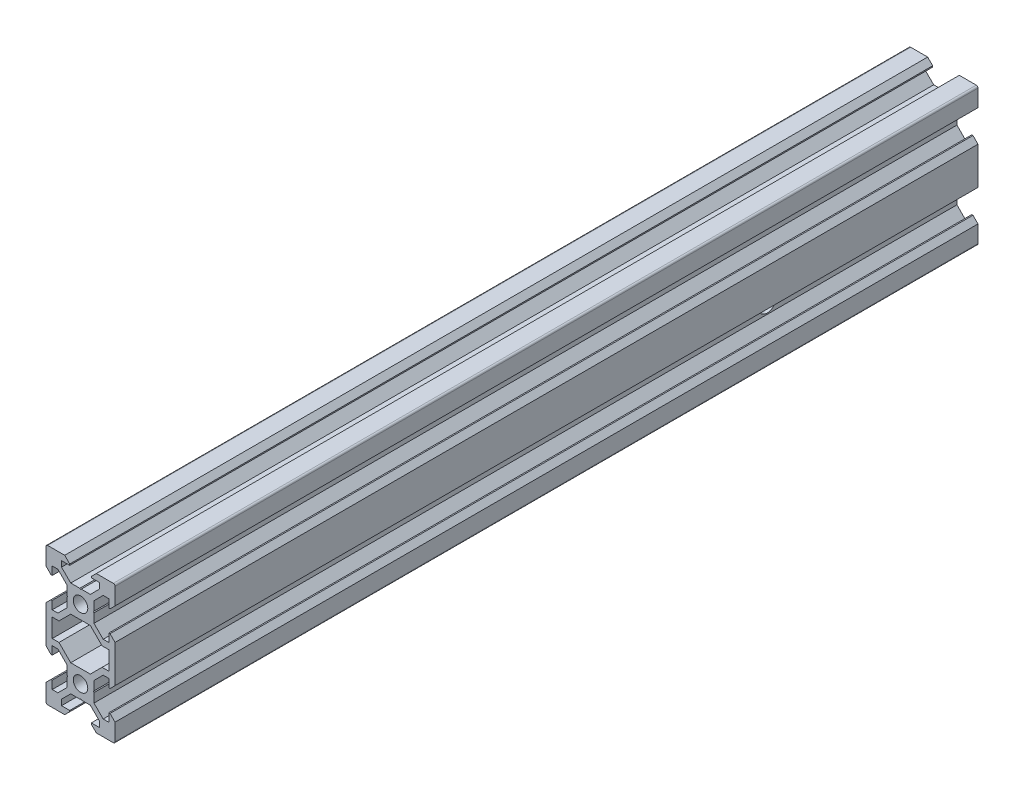
SolidWorks part; units mm, degrees
ref_plane "Plano frontal" through (0, 0, 0) normal (0, 0, 1) x (1, 0, 0)
ref_plane "Plano superior" through (0, 0, 0) normal (0, 1, 0) x (1, 0, 0)
ref_plane "Plano direito" through (0, 0, 0) normal (1, 0, 0) x (0, 0, -1)
sketch "Esboço1" plane through (0, 0, 0) normal (0, 0, 1) x (1, 0, 0)
  line L0 (8.2, -2.7) -> (8.2, 2.7)
  line L1 (8.2, 2.7) -> (6.2393, 2.7)
  line L2 (6.2393, 2.7) -> (2.8393, 6.1)
  line L3 (-2.8393, 6.1) -> (2.8393, 6.1)
  line L4 (-6.2393, 2.7) -> (-2.8393, 6.1)
  line L5 (-8.2, 2.7) -> (-6.2393, 2.7)
  line L6 (-8.2, -2.7) -> (-8.2, 2.7)
  line L7 (-8.2, -2.7) -> (-6.2393, -2.7)
  line L8 (-6.2393, -2.7) -> (-2.8393, -6.1)
  line L9 (-2.8393, -6.1) -> (2.8393, -6.1)
  line L10 (6.2393, -2.7) -> (2.8393, -6.1)
  line L11 (8.2, -2.7) -> (6.2393, -2.7)
  line L12 (3.9, 9.79) -> (3.69, 10)
  line L13 (3.69, 10) -> (3.9, 10.21)
  line L14 (3.9, 10.21) -> (3.9, 12.8393)
  line L15 (3.9, 12.8393) -> (6.5607, 15.5)
  line L16 (6.5607, 15.5) -> (8.2, 15.5)
  line L17 (8.2, 15.5) -> (8.2, 13.125)
  line L18 (8.2, 13.125) -> (8.545, 13.125)
  line L19 (8.545, 13.125) -> (10, 14.58)
  line L20 (10, 14.58) -> (10, 19.5)
  line L21 (9.5, 20) -> (4.58, 20)
  line L22 (4.58, 20) -> (3.125, 18.545)
  line L23 (3.125, 18.545) -> (3.125, 18.2)
  line L24 (3.125, 18.2) -> (5.5, 18.2)
  line L25 (5.5, 18.2) -> (5.5, 16.5607)
  line L26 (5.5, 16.5607) -> (2.8393, 13.9)
  line L27 (2.8393, 13.9) -> (0.21, 13.9)
  line L28 (0.21, 13.9) -> (0, 13.69)
  line L29 (0, 13.69) -> (-0.21, 13.9)
  line L30 (-0.21, 13.9) -> (-2.8393, 13.9)
  line L31 (-2.8393, 13.9) -> (-5.5, 16.5607)
  line L32 (-5.5, 16.5607) -> (-5.5, 18.2)
  line L33 (-5.5, 18.2) -> (-3.125, 18.2)
  line L34 (-3.125, 18.2) -> (-3.125, 18.545)
  line L35 (-3.125, 18.545) -> (-4.58, 20)
  line L36 (-4.58, 20) -> (-9.5, 20)
  line L37 (-10, 19.5) -> (-10, 14.58)
  line L38 (-10, 14.58) -> (-8.545, 13.125)
  line L39 (-8.545, 13.125) -> (-8.2, 13.125)
  line L40 (-8.2, 13.125) -> (-8.2, 15.5)
  line L41 (-8.2, 15.5) -> (-6.5607, 15.5)
  line L42 (-6.5607, 15.5) -> (-3.9, 12.8393)
  line L43 (-3.9, 12.8393) -> (-3.9, 10.21)
  line L44 (-3.9, 10.21) -> (-3.69, 10)
  line L45 (-3.69, 10) -> (-3.9, 9.79)
  line L46 (-3.9, 9.79) -> (-3.9, 7.1607)
  line L47 (-3.9, 7.1607) -> (-6.5607, 4.5)
  line L48 (-6.5607, 4.5) -> (-8.2, 4.5)
  line L49 (-8.2, 4.5) -> (-8.2, 6.875)
  line L50 (-8.2, 6.875) -> (-8.545, 6.875)
  line L51 (-8.545, 6.875) -> (-10, 5.42)
  line L52 (-10, 5.42) -> (-10, -5.42)
  line L53 (-10, -5.42) -> (-8.545, -6.875)
  line L54 (-8.545, -6.875) -> (-8.2, -6.875)
  line L55 (-8.2, -6.875) -> (-8.2, -4.5)
  line L56 (-8.2, -4.5) -> (-6.5607, -4.5)
  line L57 (-6.5607, -4.5) -> (-3.9, -7.1607)
  line L58 (-3.9, -7.1607) -> (-3.9, -9.79)
  line L59 (-3.9, -9.79) -> (-3.69, -10)
  line L60 (-3.69, -10) -> (-3.9, -10.21)
  line L61 (-3.9, -10.21) -> (-3.9, -12.8393)
  line L62 (-3.9, -12.8393) -> (-6.5607, -15.5)
  line L63 (-6.5607, -15.5) -> (-8.2, -15.5)
  line L64 (-8.2, -15.5) -> (-8.2, -13.125)
  line L65 (-8.2, -13.125) -> (-8.545, -13.125)
  line L66 (-8.545, -13.125) -> (-10, -14.58)
  line L67 (-10, -14.58) -> (-10, -19.5)
  line L68 (-9.5, -20) -> (-4.58, -20)
  line L69 (-4.58, -20) -> (-3.125, -18.545)
  line L70 (-3.125, -18.545) -> (-3.125, -18.2)
  line L71 (-3.125, -18.2) -> (-5.5, -18.2)
  line L72 (-5.5, -18.2) -> (-5.5, -16.5607)
  line L73 (-5.5, -16.5607) -> (-2.8393, -13.9)
  line L74 (-2.8393, -13.9) -> (-0.21, -13.9)
  line L75 (-0.21, -13.9) -> (0, -13.69)
  line L76 (0, -13.69) -> (0.21, -13.9)
  line L77 (0.21, -13.9) -> (2.8393, -13.9)
  line L78 (2.8393, -13.9) -> (5.5, -16.5607)
  line L79 (5.5, -16.5607) -> (5.5, -18.2)
  line L80 (5.5, -18.2) -> (3.125, -18.2)
  line L81 (3.125, -18.2) -> (3.125, -18.545)
  line L82 (3.125, -18.545) -> (4.58, -20)
  line L83 (4.58, -20) -> (9.5, -20)
  line L84 (10, -19.5) -> (10, -14.58)
  line L85 (10, -14.58) -> (8.545, -13.125)
  line L86 (8.545, -13.125) -> (8.2, -13.125)
  line L87 (8.2, -13.125) -> (8.2, -15.5)
  line L88 (8.2, -15.5) -> (6.5607, -15.5)
  line L89 (6.5607, -15.5) -> (3.9, -12.8393)
  line L90 (3.9, -12.8393) -> (3.9, -10.21)
  line L91 (3.9, -10.21) -> (3.69, -10)
  line L92 (3.69, -10) -> (3.9, -9.79)
  line L93 (3.9, -9.79) -> (3.9, -7.1607)
  line L94 (3.9, -7.1607) -> (6.5607, -4.5)
  line L95 (6.5607, -4.5) -> (8.2, -4.5)
  line L96 (8.2, -4.5) -> (8.2, -6.875)
  line L97 (8.2, -6.875) -> (8.545, -6.875)
  line L98 (8.545, -6.875) -> (10, -5.42)
  line L99 (10, -5.42) -> (10, 5.42)
  line L100 (10, 5.42) -> (8.545, 6.875)
  line L101 (8.545, 6.875) -> (8.2, 6.875)
  line L102 (8.2, 6.875) -> (8.2, 4.5)
  line L103 (8.2, 4.5) -> (6.5607, 4.5)
  line L104 (6.5607, 4.5) -> (3.9, 7.1607)
  line L105 (3.9, 7.1607) -> (3.9, 9.79)
  circle A0 centre (0, -10) radius 2.1
  circle A1 centre (0, 10) radius 2.1
  arc A2 (10, 19.5) -> (9.5, 20) centre (9.5, 19.5) ccw
  arc A3 (-9.5, 20) -> (-10, 19.5) centre (-9.5, 19.5) ccw
  arc A4 (-10, -19.5) -> (-9.5, -20) centre (-9.5, -19.5) ccw
  arc A5 (9.5, -20) -> (10, -19.5) centre (9.5, -19.5) ccw
extrude "Ressalto-extrusão1" add sketch "Esboço1" along normal blind 250
ref_plane "Plano2" through (0, 0, 0) normal (1, 0, 0) x (0, 0, -1)
ref_plane "Plano3" through (0, 0, 0) normal (0, 1, 0) x (1, 0, 0)
ref_plane "Plano4" through (0, 0, 125) normal (0, 0, -1) x (-1, 0, 0)
ref_plane "Plano5" through (0, 10, 0) normal (0, 1, 0) x (1, 0, 0)
ref_plane "Plano6" through (0, -10, 0) normal (0, 1, 0) x (1, 0, 0)
sketch "Esboço2" plane through (10, 0, 0) normal (1, 0, 0) x (0, 0, -1)
  circle A0 centre (-55, -10) radius 2.1 construction
  circle A1 centre (-55, -10) radius 2.1 construction
  circle A2 centre (-55, -10) radius 2.5
  dimension "D1" = 5
extrude "Corte-extrusão1" cut sketch "Esboço2" against normal up to surface (20 mm away) up to face at (-10, 0, 125)
